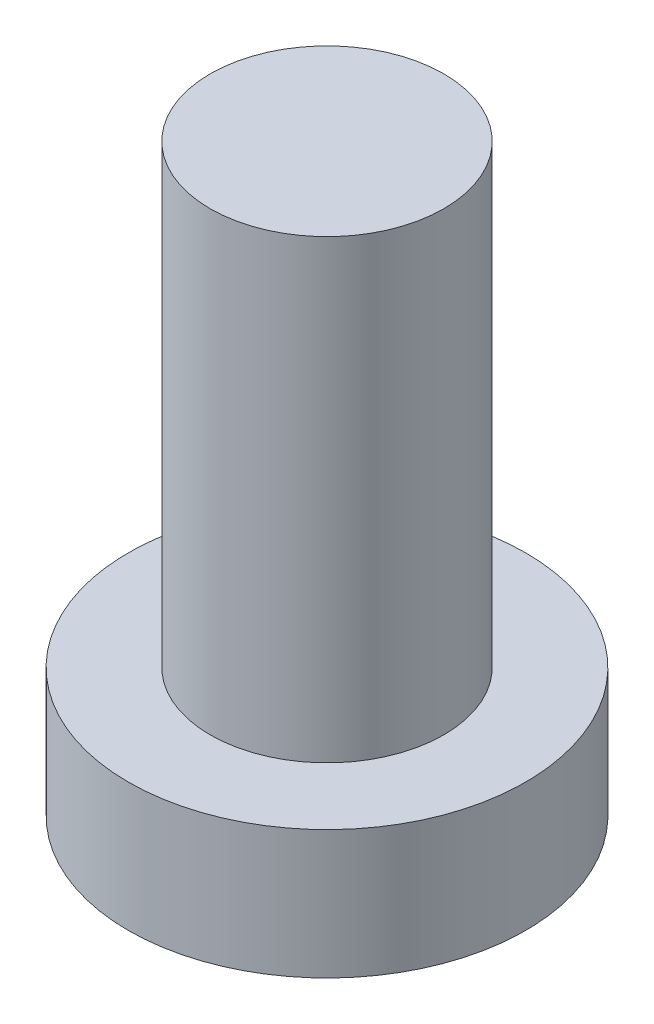
SolidWorks part; units mm, degrees
ref_plane "Front Plane" through (0, 0, 0) normal (0, 0, 1) x (1, 0, 0)
ref_plane "Top Plane" through (0, 0, 0) normal (0, 1, 0) x (1, 0, 0)
ref_plane "Right Plane" through (0, 0, 0) normal (1, 0, 0) x (0, 0, -1)
sketch "Sketch1" plane through (0, 0, 0) normal (0, 1, 0) x (1, 0, 0)
  circle A0 centre (0, 0) radius 6.8
  dimension "D1" = 13.6
extrude "Boss-Extrude1" add sketch "Sketch1" along normal blind 4.4
sketch "Sketch2" plane through (0, 4.4, 0) normal (0, 1, 0) x (1, 0, 0)
  circle A0 centre (0, 0) radius 4
  dimension "D1" = 8
extrude "Boss-Extrude2" add sketch "Sketch2" along normal blind 15.6 contours A0
